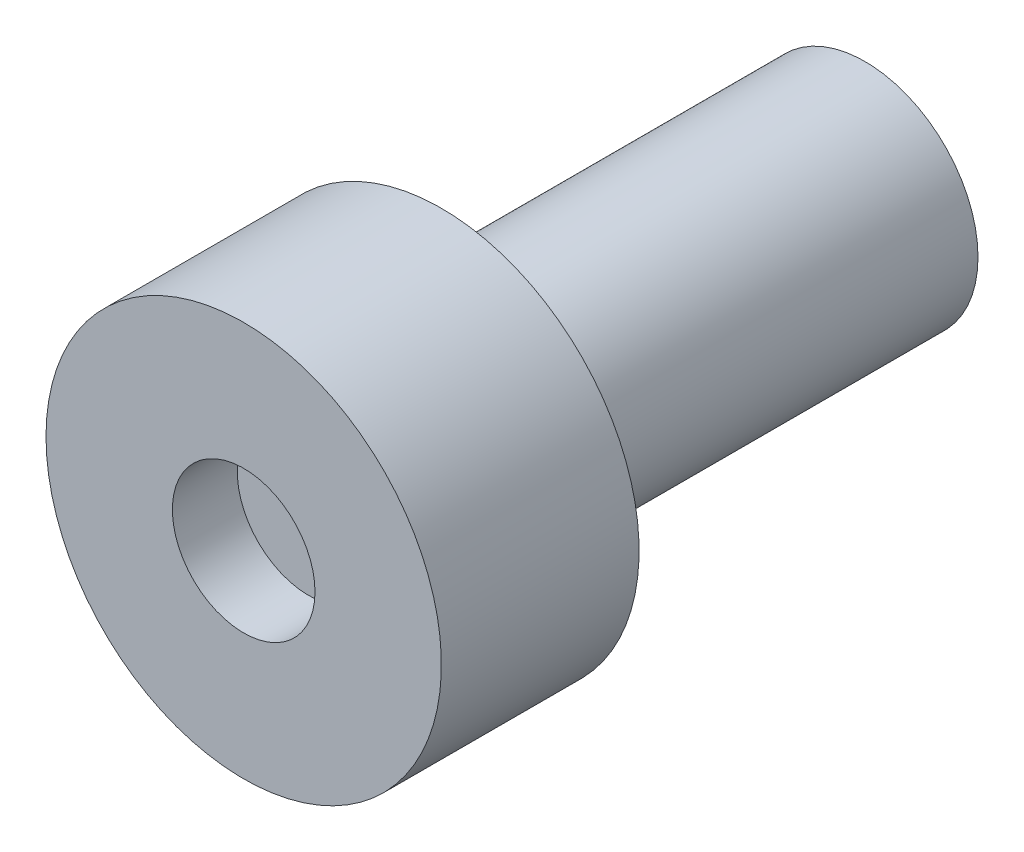
SolidWorks part; units mm, degrees
ref_plane "Front Plane" through (0, 0, 0) normal (0, 0, 1) x (1, 0, 0)
ref_plane "Top Plane" through (0, 0, 0) normal (0, 1, 0) x (1, 0, 0)
ref_plane "Right Plane" through (0, 0, 0) normal (1, 0, 0) x (0, 0, -1)
sketch "Sketch1" plane through (0, 0, 0) normal (0, 0, 1) x (1, 0, 0)
  circle A0 centre (0, 0) radius 4
  dimension "D1" = 8
extrude "Boss-Extrude1" add sketch "Sketch1" along normal blind 15
sketch "Sketch3" plane through (0, 0, 15) normal (0, 0, 1) x (1, 0, 0)
  circle A0 centre (0, 0) radius 7
  dimension "D1" = 14
extrude "Boss-Extrude3" add sketch "Sketch3" along normal blind 7
sketch "Sketch5" plane through (0, 0, 22) normal (0, 0, 1) x (1, 0, 0)
  circle A0 centre (0, 0) radius 2.525
  dimension "D1" = 5.05
extrude "Cut-Extrude2" cut sketch "Sketch5" against normal blind 2.3
